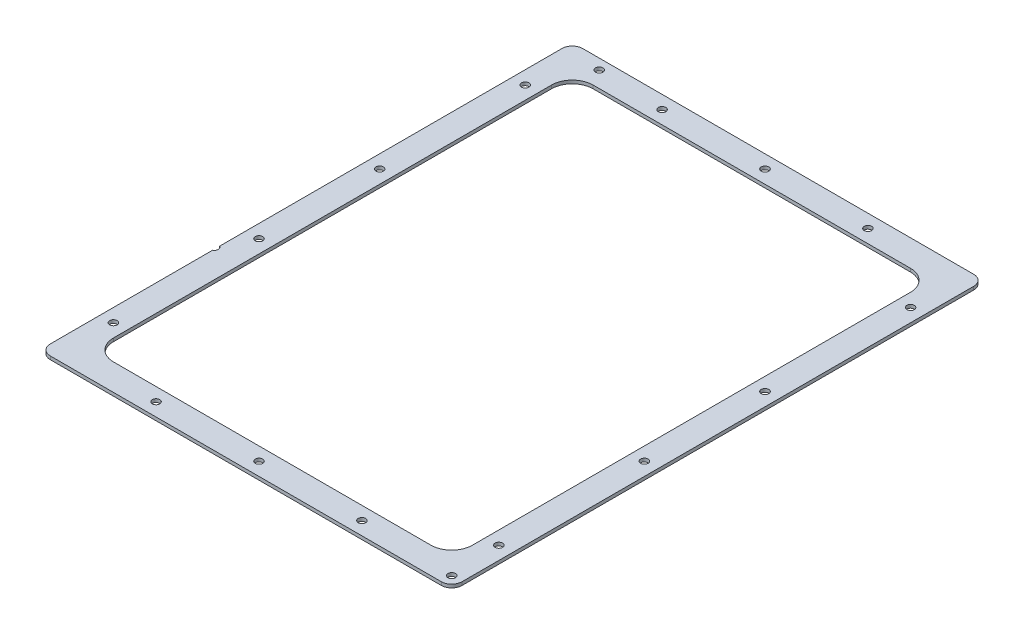
SolidWorks part; units mm, degrees
ref_plane "Front Plane" through (0, 0, 0) normal (0, 0, 1) x (1, 0, 0)
ref_plane "Top Plane" through (0, 0, 0) normal (0, 1, 0) x (1, 0, 0)
ref_plane "Right Plane" through (0, 0, 0) normal (1, 0, 0) x (0, 0, -1)
sketch "Sketch1" plane through (0, 0, 0) normal (0, 1, 0) x (1, 0, 0)
  line L1 (-99, -128) -> (99, -128)
  line L2 (-99, -128) -> (-99, 128)
  line L3 (-99, 128) -> (99, 128)
  line L4 (99, -128) -> (99, 128)
  line L5 (-99, -128) -> (99, 128) construction
  line L6 (-99, 128) -> (99, -128) construction
  line L7 (-86.3, -115.3) -> (86.3, -115.3)
  line L8 (-86.3, -115.3) -> (-86.3, 115.3)
  line L9 (-86.3, 115.3) -> (86.3, 115.3)
  line L10 (86.3, -115.3) -> (86.3, 115.3)
  line L11 (-86.3, -115.3) -> (86.3, 115.3) construction
  line L12 (-86.3, 115.3) -> (86.3, -115.3) construction
  point P0 (0, 0)
  point P6 (0, 0)
  dimension "D1" = 198
  dimension "D2" = 256
  dimension "D3" = 12.7
  dimension "D4" = 12.7
extrude "MainBody" add sketch "Sketch1" along normal blind 1.5875
hole_wizard "M3 Clearance Hole1" positions "Sketch2" profile "Sketch3" hole size "M3" standard "ANSI Metric" end condition up to next
sketch "Sketch2" plane through (0, 1.5875, 0) normal (0, 1, 0) x (1, 0, 0)
  line L0 (0, 0) -> (-99, 0) construction
  line L1 (-99, 128) -> (-99, -128) construction
  line L3 (0, 0) -> (0, 128) construction
  line L4 (99, 128) -> (-99, 128) construction
  line L6 (0, 64) -> (-99, 64) construction
  line L10 (-86.3, 99) -> (-99, 99) construction
  line L11 (-86.3, 115.3) -> (-86.3, -115.3) construction
  line L16 (-99, 108.5349) -> (0, 108.5349) construction
  line L18 (-49.5, 115.3) -> (-49.5, 128) construction
  line L19 (86.3, 115.3) -> (-86.3, 115.3) construction
  point P0 (-92.65, 99)
  point P23 (-92.65, 29)
  point P24 (-92.65, -29)
  point P25 (-92.65, -99)
  point P31 (92.65, -99)
  point P32 (92.65, -29)
  point P33 (92.65, 29)
  point P34 (92.65, 99)
  point P36 (0, 121.65)
  point P53 (-92.65, 99)
  point P66 (-49.5, 108.5349)
  point P78 (-49.5, 121.65)
  point P81 (-49.5, 121.65)
  point P93 (49.5, -121.65)
  point P94 (0, -121.65)
  point P95 (-49.5, -121.65)
  point P98 (49.5, 121.65)
  dimension "D1" = 35
sketch "Sketch3" plane through (-92.65, 1.5875, -99) normal (1, 0, 0) x (0, 0, 1)
  line L0 (0, 0) -> (0, 1.5875)
  line L1 (0, 1.5875) -> (1.8, 1.5875)
  line L2 (1.8, 1.5875) -> (1.8, 0)
  line L5 (1.8, 0) -> (0, 0)
  line L11 (0, -6.35) -> (0, 107.95) construction
  dimension "Thru Hole Dia." = 3.6
  dimension "Thru Hole Depth" = 1.5875
fillet "InsideFillet" radius 10 4 edges at (-86.3, 0.7937, 115.3) (86.3, 0.7937, 115.3) (86.3, 0.7937, -115.3) (-86.3, 0.7937, -115.3)
fillet "Fillet2" radius 5 4 edges at (-99, 0.7937, 128) (99, 0.7937, 128) (99, 0.7937, -128) (-99, 0.7937, -128)
hole_wizard "M3 Clearance Hole2" positions "Sketch4" profile "Sketch5" hole size "M3" standard "ANSI Metric" end condition through all
sketch "Sketch4" plane through (0, 1.5875, 0) normal (0, 1, 0) x (1, 0, 0)
  point P0 (-81.0723, 123)
  point P3 (106.9277, 123)
  point P6 (94, -122.975)
  point P9 (-99.7329, -43.2783)
sketch "Sketch5" plane through (-81.0723, 1.5875, -123) normal (1, 0, 0) x (0, 0, 1)
  line L0 (0, 0) -> (0, 1.5875)
  line L1 (0, 1.5875) -> (1.8, 1.5875)
  line L2 (1.8, 1.5875) -> (1.8, 0)
  line L5 (1.8, 0) -> (0, 0)
  line L11 (0, -6.35) -> (0, 107.95) construction
  dimension "Thru Hole Dia." = 3.6
  dimension "Thru Hole Depth" = 1.5875
equation "\"Width\"= 225mm"
equation "\"D1@Sketch1\"=\"InternalWidth\" - \"InnerEdgeTol\" * 2"
equation "\"Length\"= 283mm"
equation "\"WallThickness\"= 12.5mm"
equation "\"UpperWaterJacketThickness\"= 28mm"
equation "\"SpacerHeight\"= 80.2mm"
equation "\"SpacerCornerWidth\"= 10mm"
equation "\"SpacerCornerHeight\"= 60.16mm"
equation "\"SpacerPegDiameter\"= 10mm"
equation "\"SpacerPegHeight\"= 10mm"
equation "\"TubingShort\"= 110mm"
equation "\"TubingLong\"= 175mm"
equation "\"PlateLength\"= 252mm"
equation "\"PlateWidth\"= 190mm"
equation "\"PlateHoleDiameter\"= 5.9mm"
equation "\"PlateHoleBottom\"= 2mm"
equation "\"PlateHoleSide\"= 1.55mm"
equation "\"PlateHoleSpacing\"= 3.1mm"
equation "\"PlateThickness\"= 1.55mm"
equation "\"ReservoirBottom\"= 12.5mm"
equation "\"ReservoirSupportWidth\"= 12mm"
equation "\"ReservoirSupportHeight\"= 15.1mm"
equation "\"ReservoirSupportPlacementHeight\"= 50mm"
equation "\"ReservoirHoleDiameter\"= 12.7mm"
equation "\"ReservoirHoleRight\"= 25mm"
equation "\"ReservoirHoleTop\"= \"ReservoirSupportPlacementHeight\""
equation "\"ReservoirHeight\"= 90mm"
equation "\"ReservoirPortBottom\"= 4mm"
equation "\"ReservoirPortTop\"= 10mm"
equation "\"ReservoirPortWidth\"= 101mm"
equation "\"CustomSpacerWallThickness\"= 0.375in"
equation "\"CustomSpacerHeight\"= 5in"
equation "\"CustomSpacerRodHoleHeight\"= .75in"
equation "\"CustomSpacerRodHoleDiameter\"= .3125in"
equation "\"ScrewBlockSide\"= 12mm"
equation "\"ScrewBlockUpperHeight\"= 16mm"
equation "\"ScrewBlockLowerHeight\"= 16mm"
equation "\"InternalLength\"= 258mm"
equation "\"InternalWidth\"= 200mm"
equation "\"CustomSpacerPegHeight\"= 1in"
equation "\"CustomSpacerScrewBore\"=3.2mm"
equation "\"CustomSpacerScrewDepth\"=10mm"
equation "\"D2@Sketch1\"=\"InternalLength\" - \"InnerEdgeTol\" * 2"
equation "\"D4@Sketch1\"=0.5in"
equation "\"InnerEdgeTol\"= 1mm"
